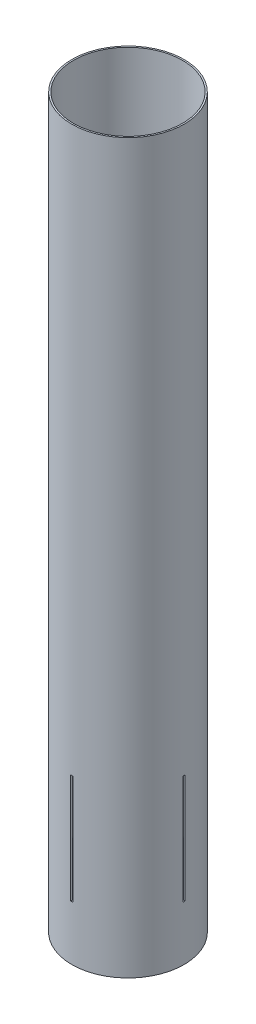
SolidWorks part; units mm, degrees
ref_plane "Front Plane" through (0, 0, 0) normal (0, 0, 1) x (1, 0, 0)
ref_plane "Top Plane" through (0, 0, 0) normal (0, 1, 0) x (1, 0, 0)
ref_plane "Right Plane" through (0, 0, 0) normal (1, 0, 0) x (0, 0, -1)
sketch "Sketch1" plane through (0, 0, 0) normal (0, 1, 0) x (1, 0, 0)
  circle A0 centre (0, 0) radius 76.2
  circle A1 centre (0, 0) radius 78.359
  dimension "D1" = 152.4
  dimension "D2" = 156.718
extrude "Boss-Extrude1" add sketch "Sketch1" along normal blind 1016
sketch "Sketch2" plane through (0, 0, 0) normal (1, 0, 0) x (0, 0, -1)
  line L0 (0, 0) -> (0, 76.2)
  line L1 (1.5875, 76.2) -> (-1.5875, 76.2)
  line L2 (1.5875, 76.2) -> (1.5875, 228.6)
  line L3 (1.5875, 228.6) -> (-1.5875, 228.6)
  line L4 (-1.5875, 76.2) -> (-1.5875, 228.6)
  line L5 (1.5875, 76.2) -> (-1.5875, 228.6) construction
  line L6 (1.5875, 228.6) -> (-1.5875, 76.2) construction
  point P0 (0, 152.4)
  dimension "D1" = 3.175
  dimension "D2" = 152.4
  dimension "D3" = 76.2
extrude "Cut-Extrude1" cut sketch "Sketch2" against normal through all contours L4 L1 L2 L3
pattern_circular "CirPattern1" count 4 over 360 about axis through (0, 0, 0) along (0, 1, 0) of "Cut-Extrude1"
equation "\"Length\"= 40in"
equation "\"D1@Boss-Extrude1\"=\"Length\""
